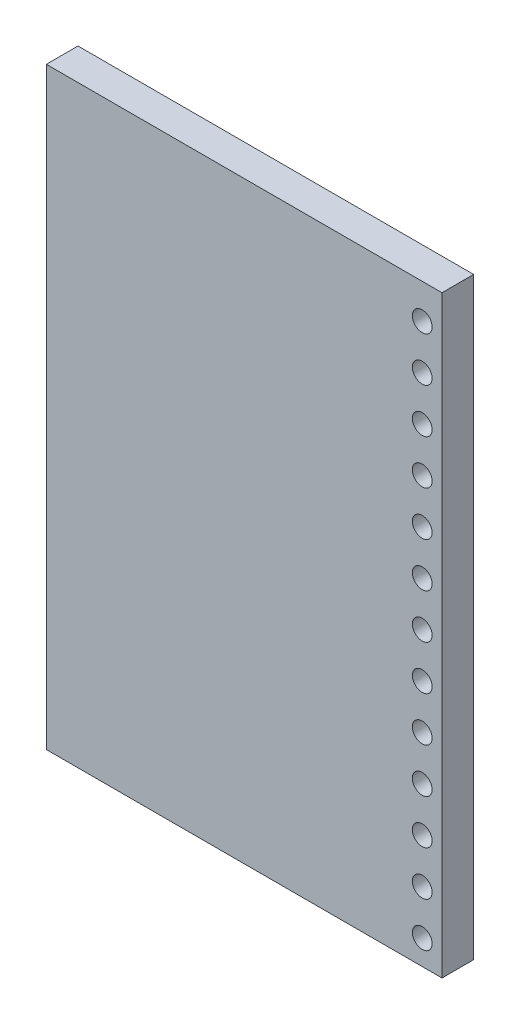
SolidWorks part; units mm, degrees
ref_plane "Front Plane" through (0, 0, 0) normal (0, 0, 1) x (1, 0, 0)
ref_plane "Top Plane" through (0, 0, 0) normal (0, 1, 0) x (1, 0, 0)
ref_plane "Right Plane" through (0, 0, 0) normal (1, 0, 0) x (0, 0, -1)
sketch "Sketch1" plane through (0, 0, 0) normal (0, 0, 1) x (1, 0, 0)
  line L1 (-100, 0) -> (100, 0)
  line L2 (-100, 0) -> (-100, 300)
  line L3 (-100, 300) -> (100, 300)
  line L4 (100, 0) -> (100, 300)
  point P4 (0, 0)
  dimension "D1" = 200
  dimension "D2" = 300
extrude "Boss-Extrude1" add sketch "Sketch1" along normal blind 16
sketch "Sketch2" plane through (0, 0, 16) normal (0, 0, 1) x (1, 0, 0)
  line L0 (100, 0) -> (100, 12.5) construction
  line L1 (100, 0) -> (100, 300) construction
  line L2 (100, 12.5) -> (90, 12.5) construction
  circle A0 centre (90, 12.5) radius 5
extrude "Cut-Extrude3" cut sketch "Sketch2" against normal through all and the other way through all
pattern_linear "LPattern1" count 13 spacing 22.5 along (0, 1, 0) of "Cut-Extrude3"
